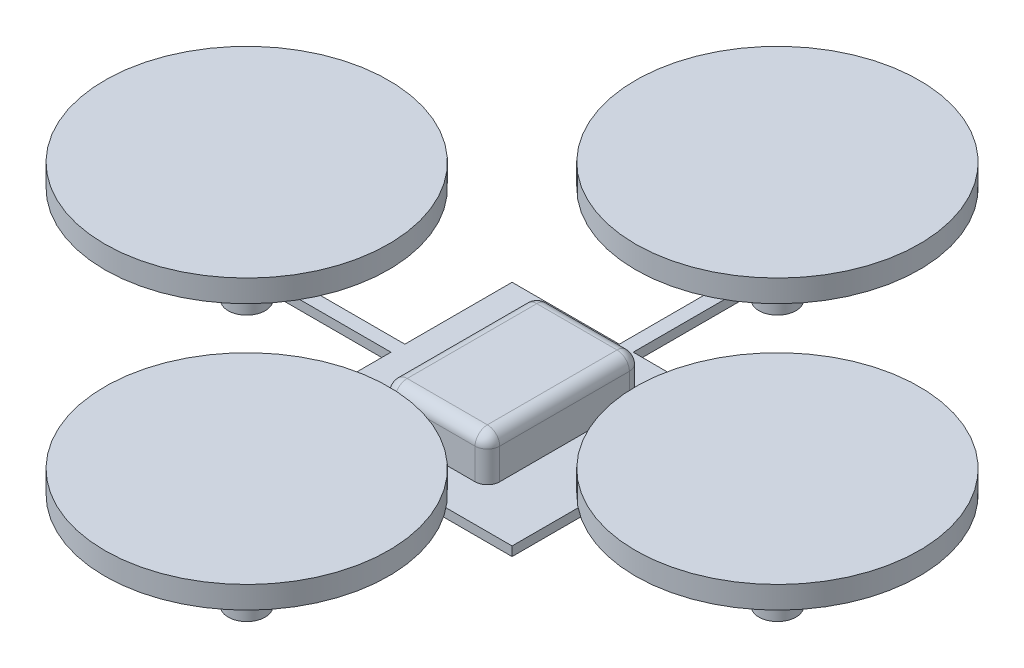
SolidWorks part; units mm, degrees
ref_plane "Front Plane" through (0, 0, 0) normal (0, 0, 1) x (1, 0, 0)
ref_plane "Top Plane" through (0, 0, 0) normal (0, 1, 0) x (1, 0, 0)
ref_plane "Right Plane" through (0, 0, 0) normal (1, 0, 0) x (0, 0, -1)
sketch "Sketch1" plane through (0, 0, 0) normal (0, 1, 0) x (1, 0, 0)
  line L0 (1.125, 18.5) -> (1.125, 40)
  line L1 (18.5, -18.5) -> (1.125, -18.5)
  line L2 (18.5, -18.5) -> (18.5, -1.125)
  line L3 (18.5, 18.5) -> (1.125, 18.5)
  line L4 (-18.5, -18.5) -> (-18.5, -1.125)
  line L5 (18.5, -18.5) -> (-18.5, 18.5) construction
  line L6 (18.5, 18.5) -> (-18.5, -18.5) construction
  line L7 (1.125, -40) -> (-1.125, -40)
  line L8 (1.125, -40) -> (1.125, -18.5)
  line L9 (1.125, 40) -> (-1.125, 40)
  line L10 (-1.125, -40) -> (-1.125, -18.5)
  line L11 (1.125, -40) -> (-1.125, 40) construction
  line L12 (1.125, 40) -> (-1.125, -40) construction
  line L13 (40, -1.125) -> (18.5, -1.125)
  line L14 (40, -1.125) -> (40, 1.125)
  line L15 (40, 1.125) -> (18.5, 1.125)
  line L16 (-40, -1.125) -> (-40, 1.125)
  line L17 (40, -1.125) -> (-40, 1.125) construction
  line L18 (40, 1.125) -> (-40, -1.125) construction
  line L19 (-1.125, 18.5) -> (-1.125, 40)
  line L20 (-18.5, -1.125) -> (-40, -1.125)
  line L21 (-18.5, 1.125) -> (-40, 1.125)
  line L22 (1.125, -0.0316) -> (1.125, 0.0316)
  line L23 (-1.125, -0.0316) -> (-1.125, 0.0316)
  line L24 (0.0316, -1.125) -> (-0.0316, -1.125)
  line L25 (0.0316, 1.125) -> (-0.0316, 1.125)
  line L26 (-18.5, 1.125) -> (-18.5, 18.5)
  line L27 (-1.125, 18.5) -> (-18.5, 18.5)
  line L28 (18.5, 1.125) -> (18.5, 18.5)
  line L29 (-1.125, -18.5) -> (-18.5, -18.5)
  point P0 (0, 0)
  point P6 (0, 0)
  point P11 (0, 0)
  dimension "D1" = 80
  dimension "D2" = 80
  dimension "D3" = 37
  dimension "D4" = 2.25
  dimension "D5" = 2.25
sketch "Sketch2" plane through (0, 0, 0) normal (0, 1, 0) x (1, 0, 0)
  line L0 (0, 43) -> (0, 0) construction
  line L1 (1.125, 40) -> (-1.125, 40) construction
  circle A0 centre (0, 43) radius 3
  circle A1 centre (43, 0) radius 3
  circle A2 centre (0, -43) radius 3
  circle A3 centre (-43, 0) radius 3
  point P15 (0, 0)
  point P16 (0, 0)
  dimension "D1" = 6
  dimension "D2" = 4
extrude "Boss-Extrude1" add sketch "Sketch1" along normal blind 1.5 contours L3 L0 L9 L19 L27 L26 L21 L16 L20 L4 L29 L10 L7 L8 L1 L2 L13 L14 L15 L28
extrude "Boss-Extrude2" add sketch "Sketch2" along normal blind 11.75 and the other way blind 4 separate body
sketch "Sketch6" plane through (0, 1.5, 0) normal (0, 1, 0) x (1, 0, 0)
  line L1 (8.5, -12.5) -> (-8.5, -12.5)
  line L2 (8.5, -12.5) -> (8.5, 12.5)
  line L3 (8.5, 12.5) -> (-8.5, 12.5)
  line L4 (-8.5, -12.5) -> (-8.5, 12.5)
  line L5 (8.5, -12.5) -> (-8.5, 12.5) construction
  line L6 (8.5, 12.5) -> (-8.5, -12.5) construction
  point P1 (0, 0)
  dimension "D1" = 17
  dimension "D2" = 25
extrude "Boss-Extrude3" add sketch "Sketch6" along normal blind 7
fillet "Fillet1" radius 2 8 edges at (0, 8.5, -12.5) (8.5, 8.5, 0) (0, 8.5, 12.5) (-8.5, 8.5, 0) (-8.5, 5, -12.5) (8.5, 5, -12.5) (8.5, 5, 12.5) (-8.5, 5, 12.5)
sketch "Sketch9" plane through (0, 11.75, 0) normal (0, 1, 0) x (1, 0, 0)
  circle A0 centre (0, 43) radius 23
  circle A1 centre (0, 43) radius 3 construction
  circle A2 centre (43, 0) radius 23
  circle A3 centre (0, -43) radius 23
  circle A4 centre (-43, 0) radius 23
  point P13 (0, 0)
  dimension "D1" = 46
  dimension "D2" = 4
extrude "Boss-Extrude4" add sketch "Sketch9" along normal blind 3.6
